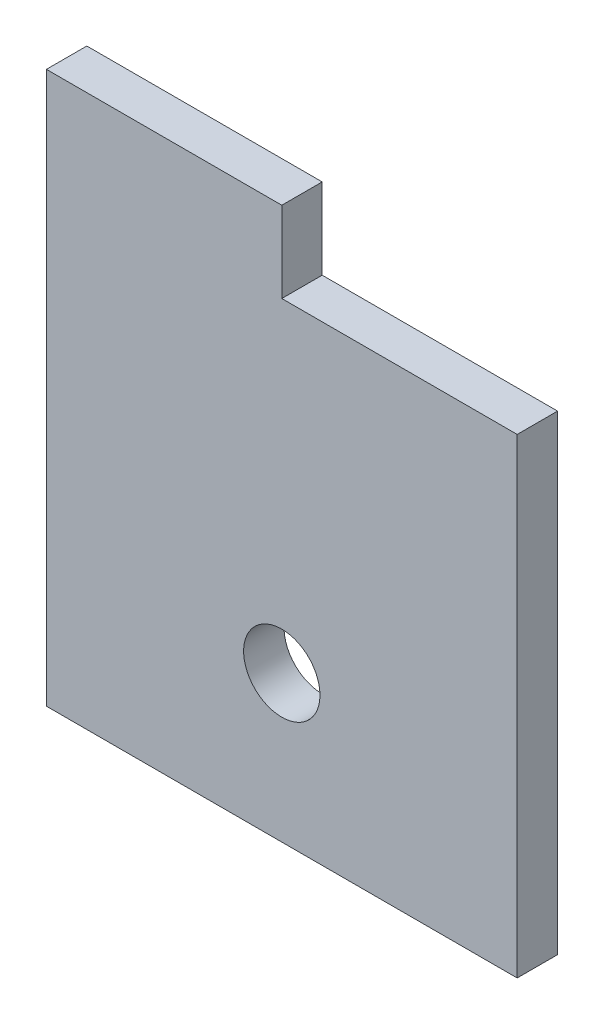
SolidWorks part; units mm, degrees
ref_plane "Front Plane" through (0, 0, 0) normal (0, 0, 1) x (1, 0, 0)
ref_plane "Top Plane" through (0, 0, 0) normal (0, 1, 0) x (1, 0, 0)
ref_plane "Right Plane" through (0, 0, 0) normal (1, 0, 0) x (0, 0, -1)
sketch "Sketch1" plane through (0, 0, 0) normal (0, 0, 1) x (1, 0, 0)
  line L1 (18.5, 0) -> (37, 0)
  line L2 (0, 0) -> (0, 37)
  line L3 (18.5, 37) -> (37, 37)
  line L4 (37, 0) -> (37, 37)
  line L7 (18.5, 0) -> (0, 0)
  line L8 (18.5, 37) -> (18.5, 43.35)
  line L9 (18.5, 43.35) -> (0, 43.35)
  line L10 (37, 0) -> (0, 37) construction
  line L11 (0, 43.35) -> (0, 37)
  line L13 (18.5, 37) -> (0, 37) construction
  circle A2 centre (18.5, 11.5) radius 2.5 construction
  circle A3 centre (18.5, 11.5) radius 3
  dimension "D4" = 18.5
  dimension "D6" = 5
  dimension "D7" = 0.5
  dimension "D1" = 37
  dimension "D2" = 37
  dimension "D3" = 6.35
  dimension "D5" = 11.5
extrude "Boss-Extrude1" add sketch "Sketch1" along normal blind 3.175
